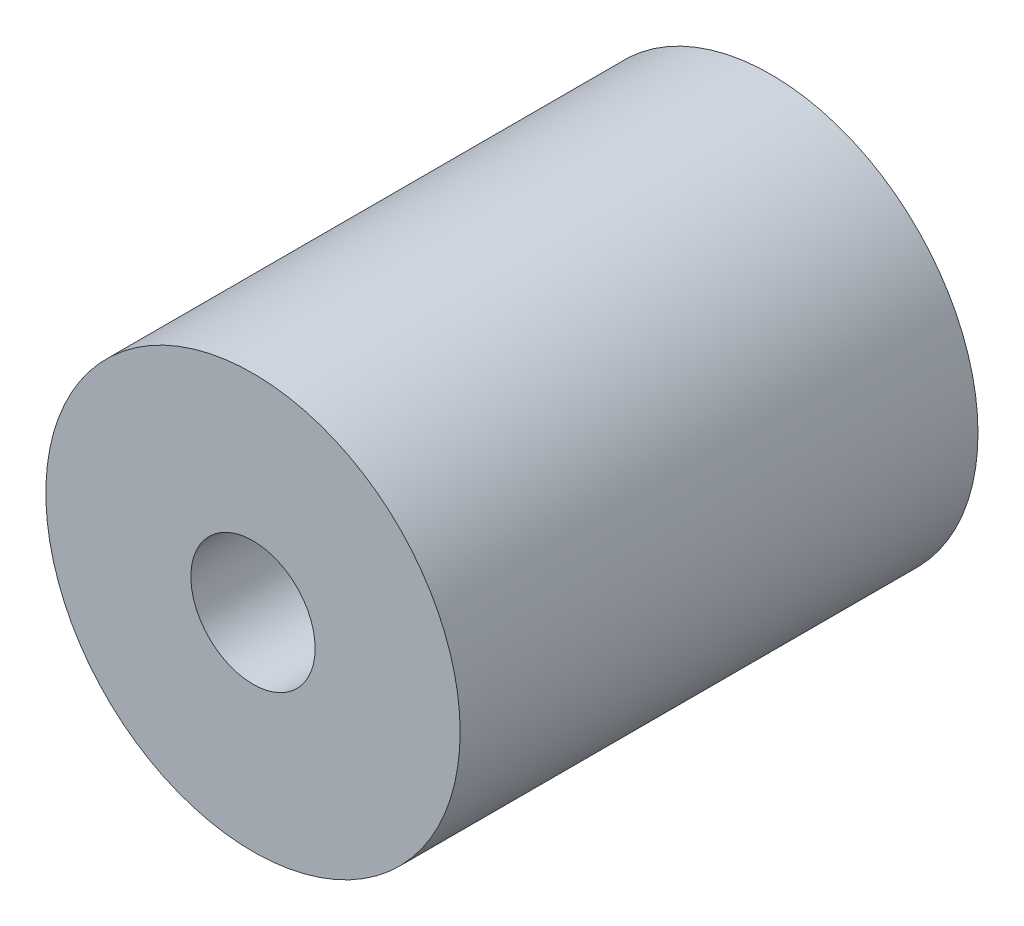
SolidWorks part; units mm, degrees
ref_plane "Front Plane" through (0, 0, 0) normal (1, 0, 0) x (0, 1, 0)
ref_plane "Top Plane" through (0, 0, 0) normal (0, 0, 1) x (0, 1, 0)
ref_plane "Right Plane" through (0, 0, 0) normal (0, 1, 0) x (-1, 0, 0)
sketch "Sketch1" plane through (0, 0, 0) normal (0, 0, 1) x (0, 1, 0)
  circle A0 centre (0, 0) radius 10
  dimension "D1" = 20
extrude "Boss-Extrude1" add sketch "Sketch1" along normal blind 25
sketch "Sketch2" plane through (0, 0, 25) normal (0, 0, 1) x (1, 0, 0)
  circle A0 centre (0, 0) radius 3
  dimension "D1" = 6
extrude "Cut-Extrude1" cut sketch "Sketch2" against normal blind 25
sketch "Sketch3" plane through (0, 0, 0) normal (0, 0, -1) x (1, 0, 0)
  circle A0 centre (0, 0) radius 4
  dimension "D1" = 8
extrude "Cut-Extrude2" cut sketch "Sketch3" against normal blind 12.5
